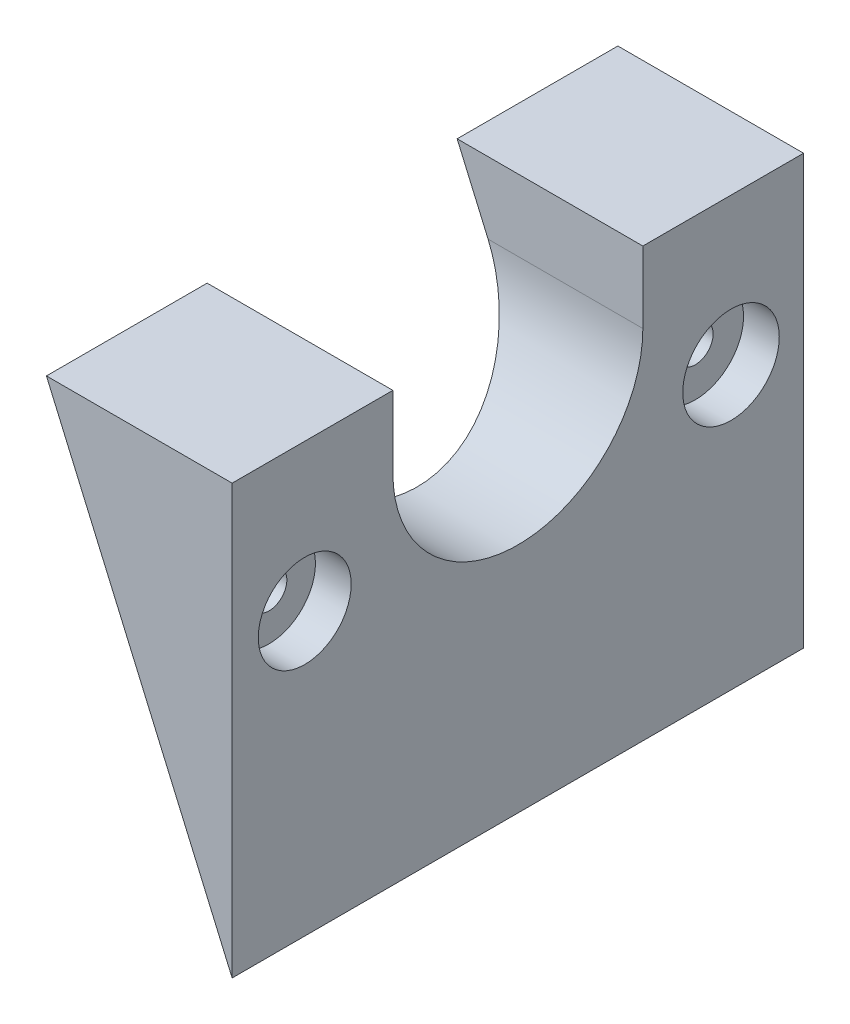
SolidWorks part; units mm, degrees
ref_plane "Front Plane" through (0, 0, 0) normal (0, 0, 1) x (1, 0, 0)
ref_plane "Top Plane" through (0, 0, 0) normal (0, 1, 0) x (1, 0, 0)
ref_plane "Right Plane" through (0, 0, 0) normal (1, 0, 0) x (0, 0, -1)
sketch "Esquisse2" plane through (0, 0, 0) normal (0, 0, 1) x (1, 0, 0)
  line L0 (0, 0) -> (0, 60)
  line L1 (0, 60) -> (-26, 60)
  line L2 (-26, 60) -> (0, 0)
  dimension "D1" = 23.429
  dimension "D2" = 60
extrude "Boss.-Extru.1" add sketch "Esquisse2" along normal blind 80
sketch "Esquisse3" plane through (0, 0, 0) normal (1, 0, 0) x (0, 0, -1)
  line L0 (-57.5, 50) -> (-57.5, 60)
  line L1 (-80, 60) -> (0, 60) construction
  line L2 (-57.5, 60) -> (-22.5, 60)
  line L3 (-22.5, 60) -> (-22.5, 50)
  line L4 (-57.5, 50) -> (-22.5, 50) construction
  line L5 (-40, 50) -> (-40, 60) construction
  arc A0 (-22.5, 50) -> (-57.5, 50) centre (-40, 50) cw
  point P0 (-40, 60)
  dimension "D1" = 17.5
  dimension "D2" = 10
extrude "Enlèv. mat.-Extru.1" cut sketch "Esquisse3" against normal through all
sketch "Esquisse4" plane through (0, 0, 0) normal (1, 0, 0) x (0, 0, -1)
  line L0 (-69.8418, 39.4295) -> (-10.1582, 39.4295) construction
  line L1 (-40, 39.4295) -> (-40, 0) construction
  line L2 (-80, 0) -> (0, 0) construction
  circle A0 centre (-69.8418, 39.4295) radius 2.5
  circle A1 centre (-10.1582, 39.4295) radius 2.5
  point P4 (0, 0)
extrude "Enlèv. mat.-Extru.2" cut sketch "Esquisse4" against normal blind 80
sketch "Esquisse6" plane through (0, 0, 0) normal (1, 0, 0) x (0, 0, -1)
  circle A0 centre (-69.8418, 39.4295) radius 6.5051
  circle A1 centre (-10.1582, 39.4295) radius 6.7558
extrude "Enlèv. mat.-Extru.3" cut sketch "Esquisse6" against normal blind 5
